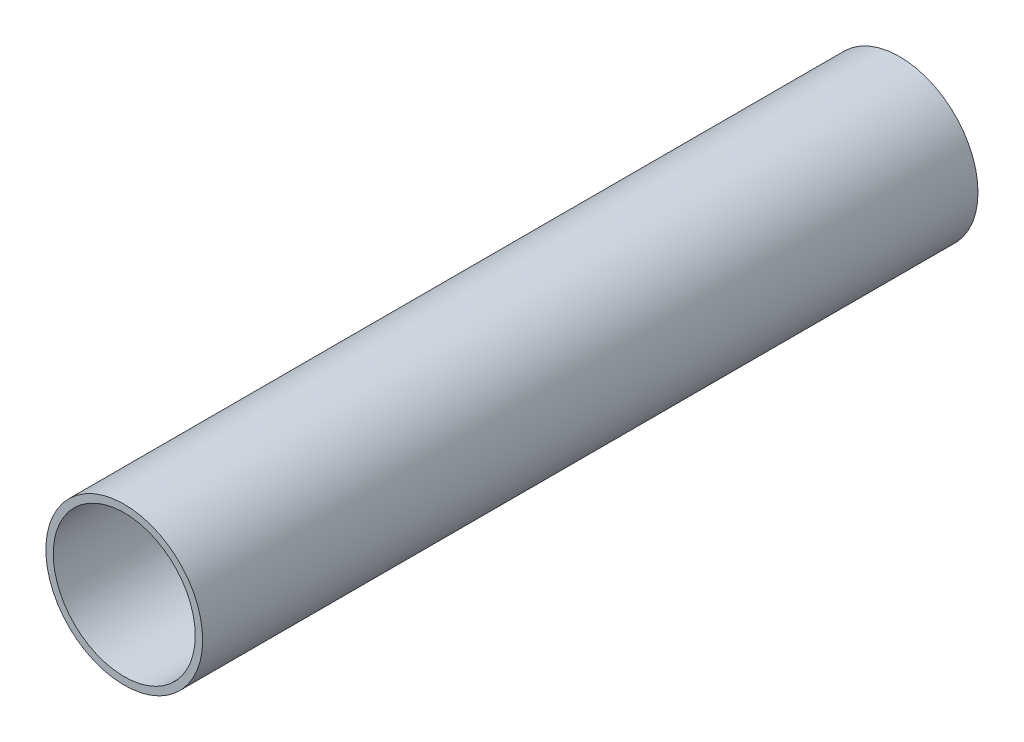
SolidWorks part; units mm, degrees
material "AISI 304"
ref_plane "Спереди" through (0, 0, 0) normal (0, 0, 1) x (1, 0, 0)
ref_plane "Сверху" through (0, 0, 0) normal (0, 1, 0) x (1, 0, 0)
ref_plane "Справа" through (0, 0, 0) normal (1, 0, 0) x (0, 0, -1)
sketch "Эскиз1" plane through (0, 0, 0) normal (0, 0, 1) x (1, 0, 0)
  circle A0 centre (0, 0) radius 31.75
  circle A1 centre (0, 0) radius 28.75
  dimension "D1" = 63.5
  dimension "D2" = 3
extrude "Бобышка-Вытянуть1" add sketch "Эскиз1" along normal mid plane 314
